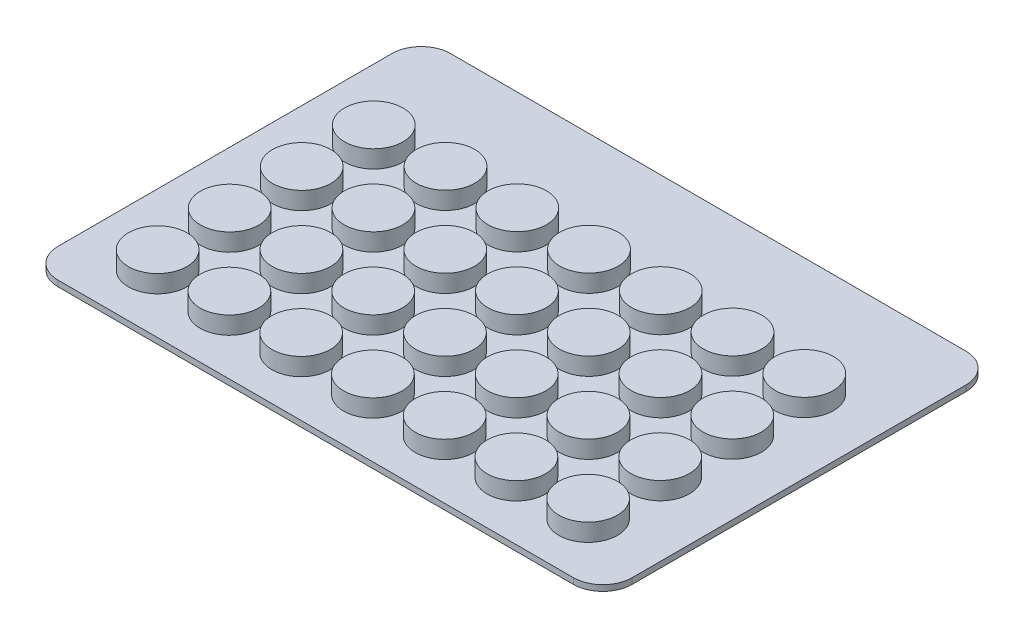
SolidWorks part; units mm, degrees
ref_plane "Front Plane" through (0, 0, 0) normal (0, 0, 1) x (1, 0, 0)
ref_plane "Top Plane" through (0, 0, 0) normal (0, 1, 0) x (1, 0, 0)
ref_plane "Right Plane" through (0, 0, 0) normal (1, 0, 0) x (0, 0, -1)
sketch "Sketch1" plane through (0, 0, 0) normal (0, 1, 0) x (1, 0, 0)
  line L1 (-44, -33.5) -> (44, -33.5)
  line L2 (-49, -28.5) -> (-49, 28.5)
  line L3 (-44, 33.5) -> (44, 33.5)
  line L4 (49, -28.5) -> (49, 28.5)
  line L5 (-49, -33.5) -> (49, 33.5) construction
  line L6 (-49, 33.5) -> (49, -33.5) construction
  arc A0 (44, -33.5) -> (49, -28.5) centre (44, -28.5) ccw
  arc A1 (-44, -33.5) -> (-49, -28.5) centre (-44, -28.5) cw
  arc A2 (-49, 28.5) -> (-44, 33.5) centre (-44, 28.5) cw
  arc A3 (44, 33.5) -> (49, 28.5) centre (44, 28.5) cw
  point P0 (0, 0)
  dimension "D3" = 5
  dimension "D1" = 98
  dimension "D2" = 67
extrude "Base" add sketch "Sketch1" along normal blind 1
sketch "Sketch2" plane through (0, 1, 0) normal (0, 1, 0) x (1, 0, 0)
  line L0 (-37, -33.5) -> (-37, -23.5) construction
  line L1 (49, -28.5) -> (49, 28.5) construction
  line L2 (-44, -33.5) -> (44, -33.5) construction
  line L4 (-37, -23.5) -> (-49, -23.5) construction
  line L5 (-49, 28.5) -> (-49, -28.5) construction
  circle A0 centre (-37, -23.5) radius 5
  circle A1 centre (-24.75, -23.5) radius 5
  circle A2 centre (-12.5, -23.5) radius 5
  circle A3 centre (-0.25, -23.5) radius 5
  circle A4 centre (12, -23.5) radius 5
  circle A5 centre (24.25, -23.5) radius 5
  circle A6 centre (36.5, -23.5) radius 5
  dimension "D3" = 10
  dimension "D1" = 12
  dimension "D2" = 10
  dimension "D5" = 12.5
  dimension "D4" = 7
extrude "Blister-Extrude" add sketch "Sketch2" along normal blind 3
pattern_linear "Blister-Pattern" count 4 spacing 12.3 along (0, 0, -1) of "Blister-Extrude"
